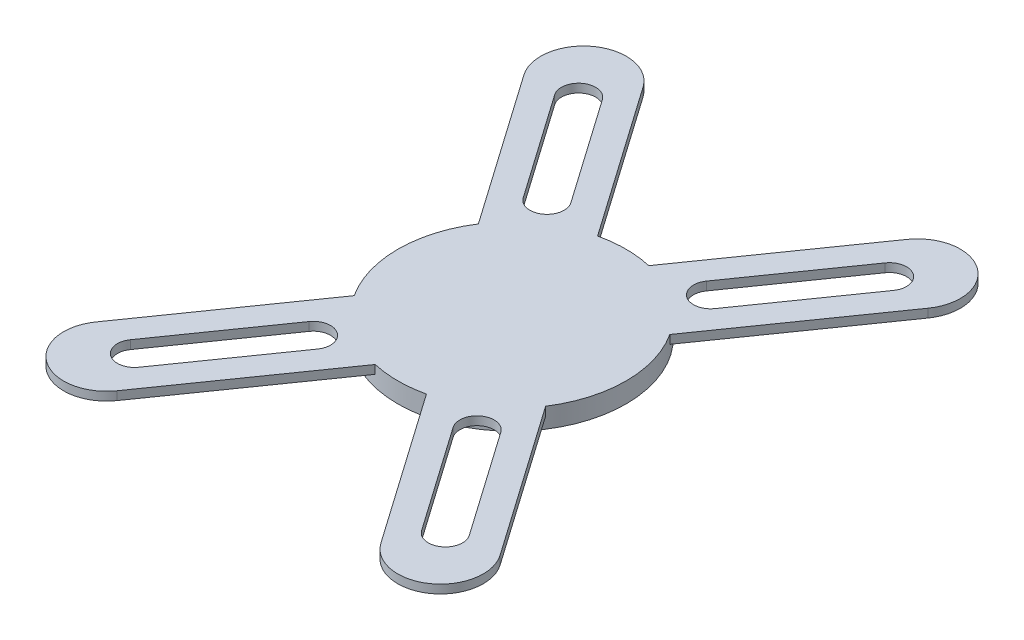
SolidWorks part; units mm, degrees
ref_plane "Front Plane" through (0, 0, 0) normal (0, 0, 1) x (1, 0, 0)
ref_plane "Top Plane" through (0, 0, 0) normal (0, 1, 0) x (1, 0, 0)
ref_plane "Right Plane" through (0, 0, 0) normal (1, 0, 0) x (0, 0, -1)
sketch "Sketch1" plane through (0, 0, 0) normal (0, 1, 0) x (1, 0, 0)
  circle A0 centre (0, 0) radius 40
  dimension "D1" = 80
extrude "Boss-Extrude1" add sketch "Sketch1" along normal blind 4
sketch "Sketch2" plane through (0, 4, 0) normal (0, 1, 0) x (1, 0, 0)
  line L0 (-1000, 0) -> (49000, 0) construction
  line L1 (70.8385, 75.0162) -> (33.5561, 21.7713)
  line L2 (-575.351, -821.6864) -> (55.5831, 79.3808) construction
  line L19 (46.264, 92.2235) -> (8.9815, 38.9786)
  line L26 (0, -1000) -> (0, 49000) construction
  line L31 (46.264, -92.2235) -> (8.9815, -38.9786)
  line L32 (70.8385, -75.0162) -> (33.5561, -21.7713)
  line L38 (-46.264, 92.2235) -> (-8.9815, 38.9786)
  line L39 (-70.8385, 75.0162) -> (-33.5561, 21.7713)
  line L40 (-70.8385, -75.0162) -> (-33.5561, -21.7713)
  line L41 (-46.264, -92.2235) -> (-8.9815, -38.9786)
  line L47 (-575.351, 821.6864) -> (55.5831, -79.3808) construction
  arc A0 (8.9815, 38.9786) -> (-8.9815, 38.9786) centre (0, 0) ccw
  arc A1 (-33.5561, 21.7713) -> (-33.5561, -21.7713) centre (0, 0) ccw
  arc A2 (-8.9815, -38.9786) -> (8.9815, -38.9786) centre (0, 0) ccw
  arc A3 (33.5561, -21.7713) -> (33.5561, 21.7713) centre (0, 0) ccw
  arc A4 (70.8385, 75.0162) -> (46.264, 92.2235) centre (58.5513, 83.6199) ccw
  arc A5 (-46.264, 92.2235) -> (-70.8385, 75.0162) centre (-58.5513, 83.6199) ccw
  arc A6 (70.8385, -75.0162) -> (46.264, -92.2235) centre (58.5513, -83.6199) cw
  arc A7 (-70.8385, -75.0162) -> (-46.264, -92.2235) centre (-58.5513, -83.6199) ccw
  dimension "D6" = 40
  dimension "D1" = 65
  dimension "D2" = 15
  dimension "D3" = 15
  dimension "D4" = 65
  dimension "D5" = 35
extrude "Boss-Extrude2" add sketch "Sketch2" along normal blind 3
sketch "Sketch3" plane through (0, 4, 0) normal (0, -1, 0) x (1, 0, 0)
  line L0 (33.5937, -37.5161) -> (59.4047, -74.378)
  line L2 (49.5748, -81.2609) -> (23.7639, -44.3991)
  line L5 (-33.5937, -37.5161) -> (-59.4047, -74.378)
  line L7 (-49.5748, -81.2609) -> (-23.7639, -44.3991)
  line L8 (23.7639, 44.3991) -> (49.5748, 81.2609)
  line L10 (59.4047, 74.378) -> (33.5937, 37.5161)
  line L13 (-23.7639, 44.3991) -> (-49.5748, 81.2609)
  line L15 (-59.4047, 74.378) -> (-33.5937, 37.5161)
  line L16 (0, 0) -> (28678.8218, 40957.6022) construction
  line L17 (0, 0) -> (-28678.8218, 40957.6022) construction
  arc A0 (33.5561, 21.7713) -> (8.9815, 38.9786) centre (0, 0) ccw construction
  arc A1 (-8.9815, 38.9786) -> (-33.5561, 21.7713) centre (0, 0) ccw construction
  arc A2 (59.4047, 74.378) -> (49.5748, 81.2609) centre (54.4898, 77.8194) ccw
  arc A3 (-49.5748, 81.2609) -> (-59.4047, 74.378) centre (-54.4898, 77.8194) ccw
  arc A4 (-33.5937, 37.5161) -> (-23.7639, 44.3991) centre (-28.6788, 40.9576) ccw
  arc A5 (23.7639, 44.3991) -> (33.5937, 37.5161) centre (28.6788, 40.9576) ccw
  arc A6 (33.5937, -37.5161) -> (23.7639, -44.3991) centre (28.6788, -40.9576) ccw
  arc A7 (49.5748, -81.2609) -> (59.4047, -74.378) centre (54.4898, -77.8194) ccw
  arc A8 (-59.4047, -74.378) -> (-49.5748, -81.2609) centre (-54.4898, -77.8194) ccw
  arc A9 (-33.5937, -37.5161) -> (-23.7639, -44.3991) centre (-28.6788, -40.9576) cw
  point P22 (22.9431, 32.7661)
  point P28 (-22.9431, 32.7661)
  point P37 (-17.3162, 79.5595)
  point P38 (-130.5565, 99.3756)
  point P39 (-36.715, -41.6087)
  point P40 (-315.7316, 19.6808)
  dimension "D6" = 50
  dimension "D8" = 50
  dimension "D1" = 6
  dimension "D2" = 50
  dimension "D3" = 6
  dimension "D4" = 50
  dimension "D5" = 6
  dimension "D7" = 6
  dimension "D9" = 45
  dimension "D10" = 45
  dimension "D11" = 45
  dimension "D12" = 45
extrude "Cut-Extrude1" cut sketch "Sketch3" against normal blind 3
